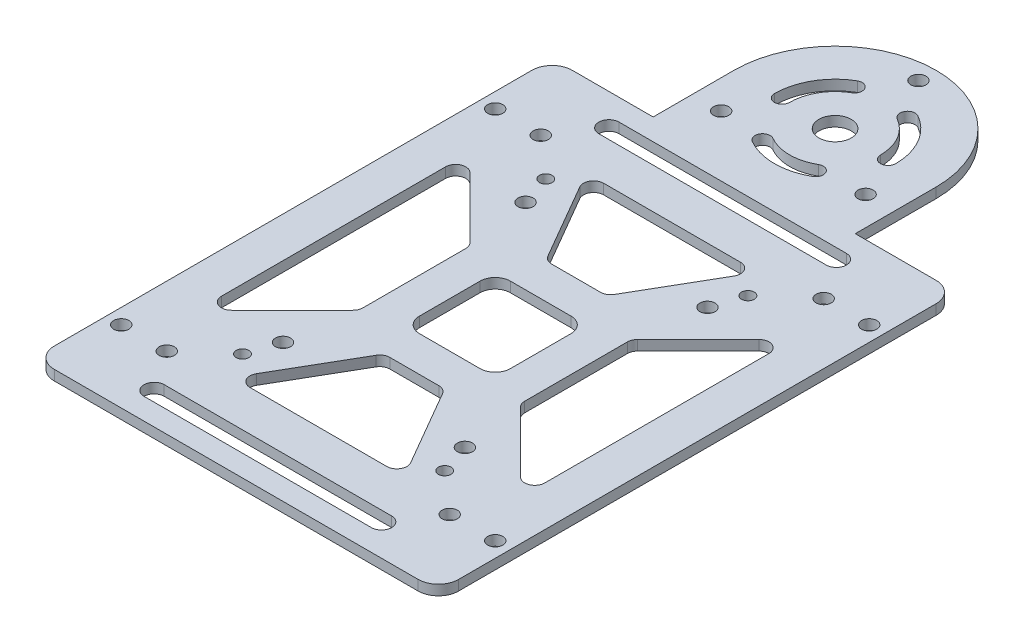
SolidWorks part; units mm, degrees
ref_plane "前视基准面" through (0, 0, 0) normal (0, 0, 1) x (1, 0, 0)
ref_plane "上视基准面" through (0, 0, 0) normal (0, 1, 0) x (1, 0, 0)
ref_plane "右视基准面" through (0, 0, 0) normal (1, 0, 0) x (0, 0, -1)
sketch "草图1" plane through (0, 0, 0) normal (0, 1, 0) x (1, 0, 0)
  line L0 (-20, 67.25) -> (-20, 51.25)
  line L1 (-36, -51.25) -> (36, -51.25)
  line L2 (-40, -47.25) -> (-40, 47.25)
  line L3 (-36, 51.25) -> (-20, 51.25)
  line L4 (40, -47.25) -> (40, 47.25)
  line L5 (-40, -51.25) -> (40, 51.25) construction
  line L6 (-40, 51.25) -> (40, -51.25) construction
  line L7 (-28, -37) -> (28, -37) construction
  line L8 (-28, -37) -> (-28, 37) construction
  line L9 (-28, 37) -> (28, 37) construction
  line L10 (28, -37) -> (28, 37) construction
  line L11 (-28, -37) -> (28, 37) construction
  line L12 (-28, 37) -> (28, -37) construction
  line L13 (-20, -30) -> (20, -30) construction
  line L14 (-20, -30) -> (-20, 30) construction
  line L15 (-20, 30) -> (20, 30) construction
  line L16 (20, -30) -> (20, 30) construction
  line L17 (-20, -30) -> (20, 30) construction
  line L18 (-20, 30) -> (20, -30) construction
  line L19 (-37, -37) -> (37, -37) construction
  line L20 (-37, -37) -> (-37, 37) construction
  line L21 (-37, 37) -> (37, 37) construction
  line L22 (37, -37) -> (37, 37) construction
  line L23 (-37, -37) -> (37, 37) construction
  line L24 (-37, 37) -> (37, -37) construction
  line L25 (20, 67.25) -> (20, 51.25)
  line L26 (20, 51.25) -> (36, 51.25)
  line L27 (7.7942, 71.75) -> (0, 67.25) construction
  line L28 (-18, -24) -> (18, -24) construction
  line L29 (-18, -24) -> (-18, 24) construction
  line L30 (-18, 24) -> (18, 24) construction
  line L31 (18, -24) -> (18, 24) construction
  line L32 (-18, -24) -> (18, 24) construction
  line L33 (-18, 24) -> (18, -24) construction
  line L34 (0, 83.75) -> (0, 67.25) construction
  line L35 (-22.5, 45) -> (22.5, 45) construction
  line L36 (-22.5, 47) -> (22.5, 47)
  line L37 (-22.5, 43) -> (22.5, 43)
  line L38 (-13.5311, 35) -> (13.5311, 35)
  line L39 (15.262, 31.9979) -> (6.5777, 16.9979)
  line L41 (16.5858, 11.5858) -> (28.5858, 23.5858)
  line L42 (32, 22.1716) -> (32, -22.1716)
  line L43 (28.5858, -23.5858) -> (16.5858, -11.5858)
  line L44 (16, -10.1716) -> (16, 10.1716)
  line L45 (-15.262, 31.9979) -> (-6.5777, 16.9979)
  line L46 (-4.8469, 16) -> (4.8469, 16)
  line L47 (4.8469, -16) -> (-4.8469, -16)
  line L48 (-15.262, -31.9979) -> (-6.5777, -16.9979)
  line L49 (13.5311, -35) -> (-13.5311, -35)
  line L50 (15.262, -31.9979) -> (6.5777, -16.9979)
  line L51 (-16.5858, -11.5858) -> (-28.5858, -23.5858)
  line L52 (-32, -22.1716) -> (-32, 22.1716)
  line L53 (-28.5858, 23.5858) -> (-16.5858, 11.5858)
  line L54 (-16, 10.1716) -> (-16, -10.1716)
  line L55 (-22.5, -45) -> (22.5, -45) construction
  line L56 (-6, -9) -> (6, -9)
  line L57 (-9, -6) -> (-9, 6)
  line L58 (-6, 9) -> (6, 9)
  line L59 (9, -6) -> (9, 6)
  line L60 (-9, -9) -> (9, 9) construction
  line L61 (-9, 9) -> (9, -9) construction
  line L62 (-22.5, -43) -> (22.5, -43)
  line L63 (-22.5, -47) -> (22.5, -47)
  circle A0 centre (-28, 37) radius 1.5
  circle A1 centre (28, 37) radius 1.5
  circle A2 centre (-28, -37) radius 1.5
  circle A3 centre (28, -37) radius 1.5
  circle A4 centre (-20, 30) radius 1.25
  circle A5 centre (20, 30) radius 1.25
  circle A6 centre (-20, -30) radius 1.25
  circle A7 centre (20, -30) radius 1.25
  circle A8 centre (37, -37) radius 1.5
  circle A9 centre (-37, -37) radius 1.5
  circle A10 centre (-37, 37) radius 1.5
  circle A11 centre (37, 37) radius 1.5
  circle A12 centre (0, 67.25) radius 3.2
  circle A13 centre (0, 67.25) radius 16.5 construction
  arc A14 (-20, 67.25) -> (20, 67.25) centre (0, 67.25) cw
  circle A15 centre (0, 83.75) radius 1.5
  circle A16 centre (14.2894, 59) radius 1.5
  circle A17 centre (-14.2894, 59) radius 1.5
  arc A18 (-36, -51.25) -> (-40, -47.25) centre (-36, -47.25) cw
  arc A19 (36, -51.25) -> (40, -47.25) centre (36, -47.25) ccw
  arc A20 (36, 51.25) -> (40, 47.25) centre (36, 47.25) cw
  arc A21 (-40, 47.25) -> (-36, 51.25) centre (-36, 47.25) cw
  circle A22 centre (-18, 24) radius 1.5
  circle A23 centre (18, 24) radius 1.5
  circle A24 centre (-18, -24) radius 1.5
  circle A25 centre (18, -24) radius 1.5
  arc A26 (4.5, 75.0442) -> (9, 67.25) centre (0, 67.25) cw
  arc A27 (6, 77.6423) -> (12, 67.25) centre (0, 67.25) cw
  arc A28 (6, 77.6423) -> (4.5, 75.0442) centre (5.25, 76.3433) ccw
  arc A29 (12, 67.25) -> (9, 67.25) centre (10.5, 67.25) cw
  arc A30 (-6, 56.8577) -> (-4.5, 59.4558) centre (-5.25, 58.1567) cw
  arc A31 (4.5, 59.4558) -> (-4.5, 59.4558) centre (0, 67.25) cw
  arc A32 (6, 56.8577) -> (4.5, 59.4558) centre (5.25, 58.1567) ccw
  arc A33 (6, 56.8577) -> (-6, 56.8577) centre (0, 67.25) cw
  arc A34 (-6, 77.6423) -> (-4.5, 75.0442) centre (-5.25, 76.3433) cw
  arc A35 (-9, 67.25) -> (-4.5, 75.0442) centre (0, 67.25) cw
  arc A36 (-12, 67.25) -> (-9, 67.25) centre (-10.5, 67.25) ccw
  arc A37 (-12, 67.25) -> (-6, 77.6423) centre (0, 67.25) cw
  arc A38 (-22.5, 47) -> (-22.5, 43) centre (-22.5, 45) ccw
  arc A39 (22.5, 43) -> (22.5, 47) centre (22.5, 45) ccw
  arc A40 (32, -22.1716) -> (28.5858, -23.5858) centre (30, -22.1716) cw
  arc A41 (28.5858, 23.5858) -> (32, 22.1716) centre (30, 22.1716) cw
  arc A42 (16.5858, -11.5858) -> (16, -10.1716) centre (18, -10.1716) cw
  arc A43 (16, 10.1716) -> (16.5858, 11.5858) centre (18, 10.1716) cw
  arc A44 (13.5311, 35) -> (15.262, 31.9979) centre (13.5311, 33) cw
  arc A45 (6.5777, 16.9979) -> (4.8469, 16) centre (4.8469, 18) cw
  arc A46 (-6.5777, 16.9979) -> (-4.8469, 16) centre (-4.8469, 18) ccw
  arc A47 (-13.5311, 35) -> (-15.262, 31.9979) centre (-13.5311, 33) ccw
  arc A48 (6.5777, -16.9979) -> (4.8469, -16) centre (4.8469, -18) ccw
  arc A49 (-6.5777, -16.9979) -> (-4.8469, -16) centre (-4.8469, -18) cw
  arc A50 (-13.5311, -35) -> (-15.262, -31.9979) centre (-13.5311, -33) cw
  arc A51 (13.5311, -35) -> (15.262, -31.9979) centre (13.5311, -33) ccw
  arc A52 (-16, -10.1716) -> (-16.5858, -11.5858) centre (-18, -10.1716) cw
  arc A53 (-28.5858, -23.5858) -> (-32, -22.1716) centre (-30, -22.1716) cw
  arc A54 (-32, 22.1716) -> (-28.5858, 23.5858) centre (-30, 22.1716) cw
  arc A55 (-16.5858, 11.5858) -> (-16, 10.1716) centre (-18, 10.1716) cw
  arc A56 (6, 9) -> (9, 6) centre (6, 6) cw
  arc A57 (6, -9) -> (9, -6) centre (6, -6) ccw
  arc A58 (-6, -9) -> (-9, -6) centre (-6, -6) cw
  arc A59 (-9, 6) -> (-6, 9) centre (-6, 6) cw
  arc A60 (-22.5, -43) -> (-22.5, -47) centre (-22.5, -45) ccw
  arc A61 (22.5, -47) -> (22.5, -43) centre (22.5, -45) ccw
  point P0 (0, 0)
  point P6 (0, 0)
  point P15 (0, 0)
  point P24 (0, 0)
  point P38 (0, 0)
  point P48 (0, 67.25)
  point P76 (10.3923, 73.25)
  point P90 (0, 67.25)
  point P92 (0, 45)
  point P115 (0, 16)
  point P116 (0, 35)
  point P117 (16, 0)
  point P118 (32, 0)
  point P121 (32, -27)
  point P124 (32, 27)
  point P127 (16, -11)
  point P130 (16, 11)
  point P133 (17, 35)
  point P136 (6, 16)
  point P139 (-6, 16)
  point P142 (-17, 35)
  point P144 (0, -16)
  point P159 (0, 0)
  point P161 (0, 0)
  point P178 (0, -45)
  dimension "D7" = 3
  dimension "D8" = 2.5
  dimension "D11" = 3
  dimension "D13" = 6.4
  dimension "D14" = 33
  dimension "D15" = 20
  dimension "D16" = 3
  dimension "D18" = 4
  dimension "D21" = 3
  dimension "D23" = 9
  dimension "D24" = 3
  dimension "D38" = 2
  dimension "D40" = 18
  dimension "D42" = 3
  dimension "D1" = 102.5
  dimension "D2" = 80
  dimension "D3" = 74
  dimension "D4" = 56
  dimension "D5" = 60
  dimension "D6" = 40
  dimension "D9" = 74
  dimension "D10" = 74
  dimension "D12" = 16
  dimension "D19" = 48
  dimension "D20" = 36
  dimension "D22" = 60
  dimension "D26" = 60
  dimension "D27" = 45
  dimension "D28" = 4
  dimension "D29" = 45
  dimension "D30" = 16
  dimension "D31" = 19
  dimension "D32" = 12
  dimension "D33" = 34
  dimension "D34" = 16
  dimension "D35" = 22
  dimension "D36" = 16
  dimension "D37" = 54
  dimension "D41" = 18
  dimension "D43" = 4
  dimension "D44" = 45
  dimension "D45" = 45
  dimension "D17" = 3
  dimension "D25" = 3
  dimension "D39" = 2
extrude "凸台-拉伸1" add sketch "草图1" along normal blind 2
